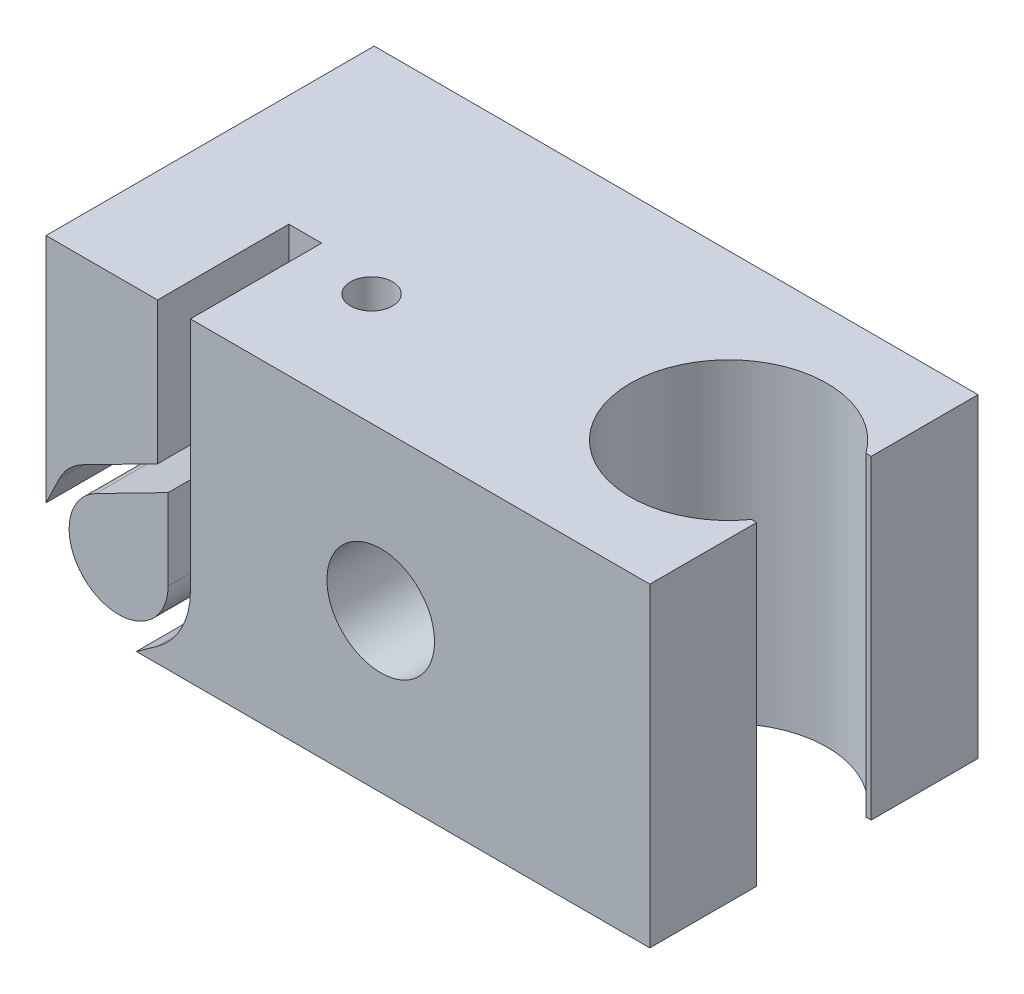
SolidWorks part; units mm, degrees
material "PET"
ref_plane "Front Plane" through (0, 0, 0) normal (0, 0, 1) x (1, 0, 0)
ref_plane "Top Plane" through (0, 0, 0) normal (0, 1, 0) x (1, 0, 0)
ref_plane "Right Plane" through (0, 0, 0) normal (1, 0, 0) x (0, 0, -1)
sketch "Sketch1" plane through (0, 0, 0) normal (0, 1, 0) x (1, 0, 0)
  line L1 (0, 12.5) -> (-10, 12.5)
  line L2 (-10, -12.5) -> (-20, -12.5)
  line L3 (0, -12.5) -> (-10, -12.5)
  line L4 (-10, 12.5) -> (-10, -12.5)
  line L5 (-10, -12.5) -> (-10, 12.5)
  line L6 (-10, 12.5) -> (-20, 12.5)
  line L7 (-20, -12.5) -> (-20, 12.5)
  line L8 (0, 12.5) -> (12.5, 12.5)
  line L10 (0, -12.5) -> (12.5, -12.5)
  line L11 (12.5, 12.5) -> (12.5, -12.5)
  circle A0 centre (0, 0) radius 7.5
  arc A1 (0, -12.5) -> (0, 12.5) centre (0, 0) ccw construction
  dimension "D1" = 15
  dimension "D2" = 12.5
  dimension "D3" = 10
  dimension "D4" = 10
extrude "Boss-Extrude1" add sketch "Sketch1" along normal blind 24 contours L3 A1 L1 L4 A0
sketch "Sketch5" plane through (0, 0, 0) normal (0, -1, 0) x (1, 0, 0)
  line L0 (12.5, -12.5) -> (12.5, 12.5) construction
  line L1 (12.5, 12.5) -> (6.5, 12.5)
  line L2 (12.5, 12.5) -> (12.5, -12.5)
  line L3 (12.5, -12.5) -> (6.5, -12.5)
  line L4 (6.5, 12.5) -> (6.5, 4.3635)
  line L6 (6.5, -4.3635) -> (6.5, -12.5)
  line L7 (6.5, 4.3635) -> (6.1, 4.3635)
  line L8 (12.5, 12.5) -> (-10, 12.5) construction
  line L9 (6.5, -4.3635) -> (6.1, -4.3635)
  line L10 (6.1, 4.3635) -> (6.1, -4.3635)
  line L11 (12.5, -12.5) -> (-10, -12.5) construction
  circle A3 centre (0, 0) radius 7.5 construction
  point P15 (6.1, 0)
  point P16 (12.5, 0)
  dimension "D1" = 6
  dimension "D2" = 0.4
  dimension "D3" = 0
extrude "Cut-Extrude4" cut sketch "Sketch5" against normal through all
sketch "Sketch7" plane through (0, 0, 0) normal (0, -1, 0) x (1, 0, 0)
  line L1 (0, 12.5) -> (-10, 12.5)
  line L2 (-10, -12.5) -> (-20, -12.5)
  line L3 (0, -12.5) -> (-10, -12.5)
  line L4 (-10, 12.5) -> (-10, -12.5)
  line L5 (-10, -12.5) -> (-10, 12.5)
  line L6 (-10, 12.5) -> (-20, 12.5)
  line L7 (-20, -12.5) -> (-20, 12.5)
  circle A0 centre (0, 0) radius 7.5
  arc A1 (0, -12.5) -> (0, 12.5) centre (0, 0) ccw
  line M21 (-10, 12.5) -> (-10, -12.5)
  dimension "D1" = 15
  dimension "D2" = 12.5
  dimension "D3" = 10
  dimension "D4" = 10
extrude "Boss-Extrude2" add sketch "Sketch7" against normal blind 24 contours L7 L2 L6 M21
sketch "Sketch8" plane through (0, 0, 12.5) normal (0, 0, 1) x (1, 0, 0)
  line L0 (-20, 12) -> (6.5, 12) construction
  line L1 (-20, 24) -> (-20, 0) construction
  line L3 (6.5, 24) -> (6.5, 0) construction
  circle A0 centre (-14, 12) radius 4.1
  dimension "D1" = 8.2
  dimension "D2" = 6
extrude "Cut-Extrude5" cut sketch "Sketch8" against normal blind 48
sketch "Sketch135" plane through (0, 0, -12.5) normal (0, 0, -1) x (-1, 0, 0)
  line L0 (-6.5, 0) -> (20, 0) construction
  line L1 (20, 24) -> (39.5, 24)
  line L2 (20, 24) -> (20, 0)
  line L3 (20, 0) -> (39.5, 0)
  line L4 (39.5, 24) -> (39.5, 0)
  dimension "D1" = 19.5
extrude "Boss-Extrude66" add sketch "Sketch135" against normal blind 15
sketch "Sketch136" plane through (0, 0, 2.5) normal (0, 0, 1) x (1, 0, 0)
  line L0 (-26.5, 0) -> (-30.65, 0)
  line L1 (-26.5, 24) -> (-28.5, 24)
  line L2 (-26.5, 24) -> (-26.5, 0)
  line L3 (-39.5, 24) -> (-20, 24) construction
  line L4 (-28.5, 24) -> (-28.5, 6.0276)
  line L5 (-31, 24) -> (-39.5, 24)
  line L6 (-31, 24) -> (-31, 13.19)
  line L7 (-30.2, 5.5304) -> (-30.2, 11.6897)
  line L8 (-39.5, 24) -> (-39.5, 8.68)
  line L9 (-30.2, 11.6897) -> (-35.6851, 8.8877)
  line L10 (-31, 13.19) -> (-36.71, 10.2731)
  line L11 (-38.4927, 8.4496) -> (-39.5, 6.3626)
  line L12 (-39.5, 6.3626) -> (-39.5, 8.68)
  line L13 (-31.0158, 1.1429) -> (-32.6182, 0)
  line L14 (-32.6182, 0) -> (-30.65, 0)
  arc A1 (-31.0158, 1.1429) -> (-28.5, 6.0276) centre (-34.5, 6.0276) ccw
  arc A3 (-36.71, 10.2731) -> (-38.4927, 8.4496) centre (-34.8903, 6.711) ccw
  arc A4 (-35.6851, 8.8877) -> (-30.2, 5.5304) centre (-33.97, 5.5304) ccw
  dimension "D4" = 35.499
  dimension "D5" = 12
  dimension "D10" = 25.764
  dimension "D13" = 8
  dimension "D12" = 7.54
  dimension "D1" = 2
  dimension "D2" = 24
  dimension "D3" = 4.15
  dimension "D6" = 8.5
  dimension "D7" = 10.81
  dimension "D8" = 2.5
  dimension "D9" = 15.32
  dimension "D11" = 5.71
  dimension "D14" = 1.7
  dimension "D15" = 1.7
  dimension "D16" = 2.3174
  dimension "D17" = 1.9682
extrude "Boss-Extrude67" add sketch "Sketch136" along normal blind 10
sketch "Sketch137" plane through (0, 0, 2.5) normal (0, 0, 1) x (1, 0, 0)
  line L1 (-20, 24) -> (-26.5, 24)
  line L2 (-20, 24) -> (-20, 0)
  line L3 (-20, 0) -> (-26.5, 0)
  line L4 (-26.5, 24) -> (-26.5, 0)
extrude "Cut-Extrude6" cut sketch "Sketch137" against normal blind 5.3
sketch "Sketch138" plane through (0, 0, 0) normal (0, -1, 0) x (1, 0, 0)
  line L0 (-26.5, 12.5) -> (-26.5, -2.8) construction
  line L1 (-20, 12.5) -> (-26.5, 12.5)
  line L2 (-20, 12.5) -> (-20, 10.7)
  line L3 (-20, 10.7) -> (-26.5, 10.7)
  line L4 (-26.5, 12.5) -> (-26.5, 10.7)
  dimension "D1" = 1.8
extrude "Boss-Extrude68" add sketch "Sketch138" against normal up to surface (24 mm away) up to face at (-16.65, 24, 3.0875)
sketch "Sketch139" plane through (0, 24, 0) normal (0, 1, 0) x (1, 0, 0)
  line L0 (-20, 2.8) -> (-26.5, -10.7) construction
  line L1 (-20, 2.8) -> (-26.5, 2.8)
  line L2 (-20, 2.8) -> (-20, -10.7)
  line L3 (-20, -10.7) -> (-26.5, -10.7)
  line L4 (-26.5, 2.8) -> (-26.5, -10.7)
  circle A0 centre (-23.25, -3.95) radius 1.6
  dimension "D1" = 3.2
extrude "Boss-Extrude69" add sketch "Sketch139" against normal blind 5
